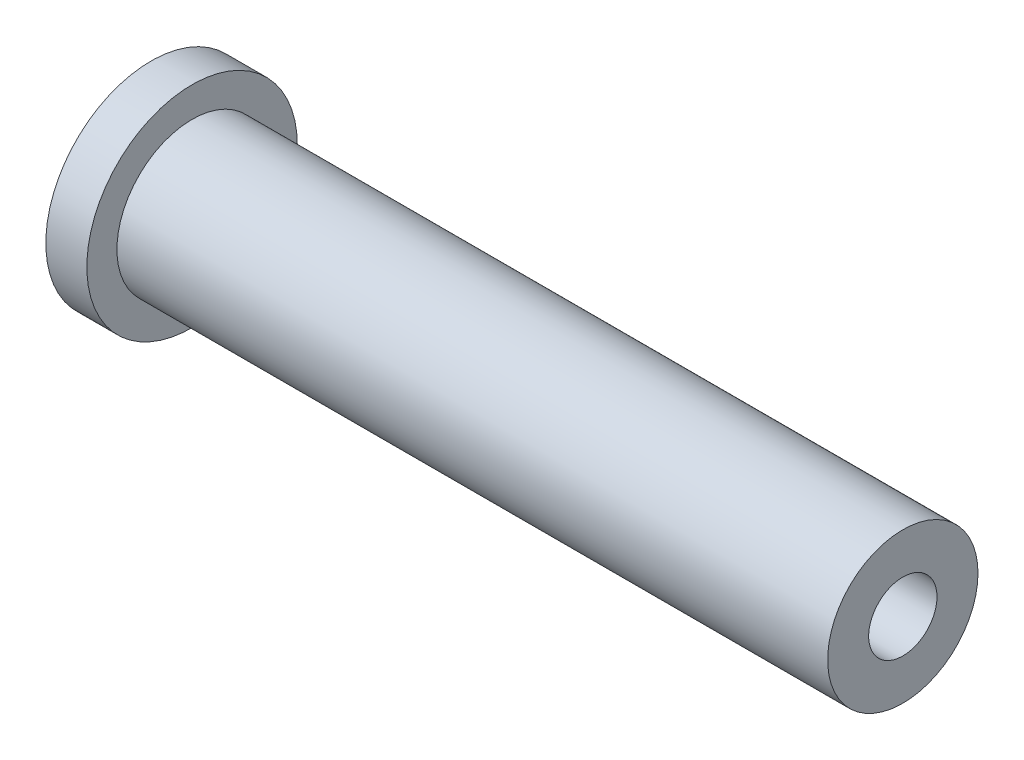
SolidWorks part; units mm, degrees
material "AISI 1020"
ref_plane "Front Plane" through (0, 0, 0) normal (0, 0, 1) x (1, 0, 0)
ref_plane "Top Plane" through (0, 0, 0) normal (0, 1, 0) x (1, 0, 0)
ref_plane "Right Plane" through (0, 0, 0) normal (1, 0, 0) x (0, 0, -1)
sketch "Sketch1" plane through (0, 0, 0) normal (0, 0, 1) x (1, 0, 0)
  line L0 (0, 0) -> (0, 7.7)
  line L1 (0, 7.7) -> (3, 7.7)
  line L2 (3, 7.7) -> (3, 5.5)
  line L3 (3, 5.5) -> (55, 5.5)
  line L4 (55, 5.5) -> (55, 0)
  line L5 (55, 0) -> (0, 0)
  line L6 (0, 0) -> (-5.4432, 0) construction
  dimension "D1" = 52
  dimension "D2" = 3
  dimension "D3" = 11
  dimension "D4" = 15.4
revolve "Revolve1" add sketch "Sketch1" angle 360 about L6
sketch "Sketch2" plane through (55, 0, 0) normal (1, 0, 0) x (0, 0, -1)
  circle A0 centre (0, 0) radius 2.55
  dimension "D1" = 5.1
hole_wizard "Broca de rosquear para tarraxa de M61" positions "Esboço1" profile "Esboço2" hole size "M6" standard "ISO"
sketch "Esboço1" plane through (55, 0, 0) normal (1, 0, 0) x (0, 0, -1)
  point P0 (0, 0)
sketch "Esboço2" plane through (55, 0, 0) normal (0, 1, 0) x (0, 0, -1)
  line L0 (0, 0) -> (0, 13.5022)
  line L1 (0, 13.5022) -> (2.5, 12)
  line L2 (2.5, 12) -> (2.5, 0)
  line L5 (2.5, 0) -> (0, 0)
  line L10 (0, 13.5022) -> (-2.5, 12) construction
  line L11 (0, -6.35) -> (0, 107.95) construction
  dimension "Hole Dia." = 5
  dimension "Hole Depth" = 12
  dimension "Drill Angle" = 118
cosmetic thread "Representação de rosca1" parameters "D1"=10, "D2"=6
